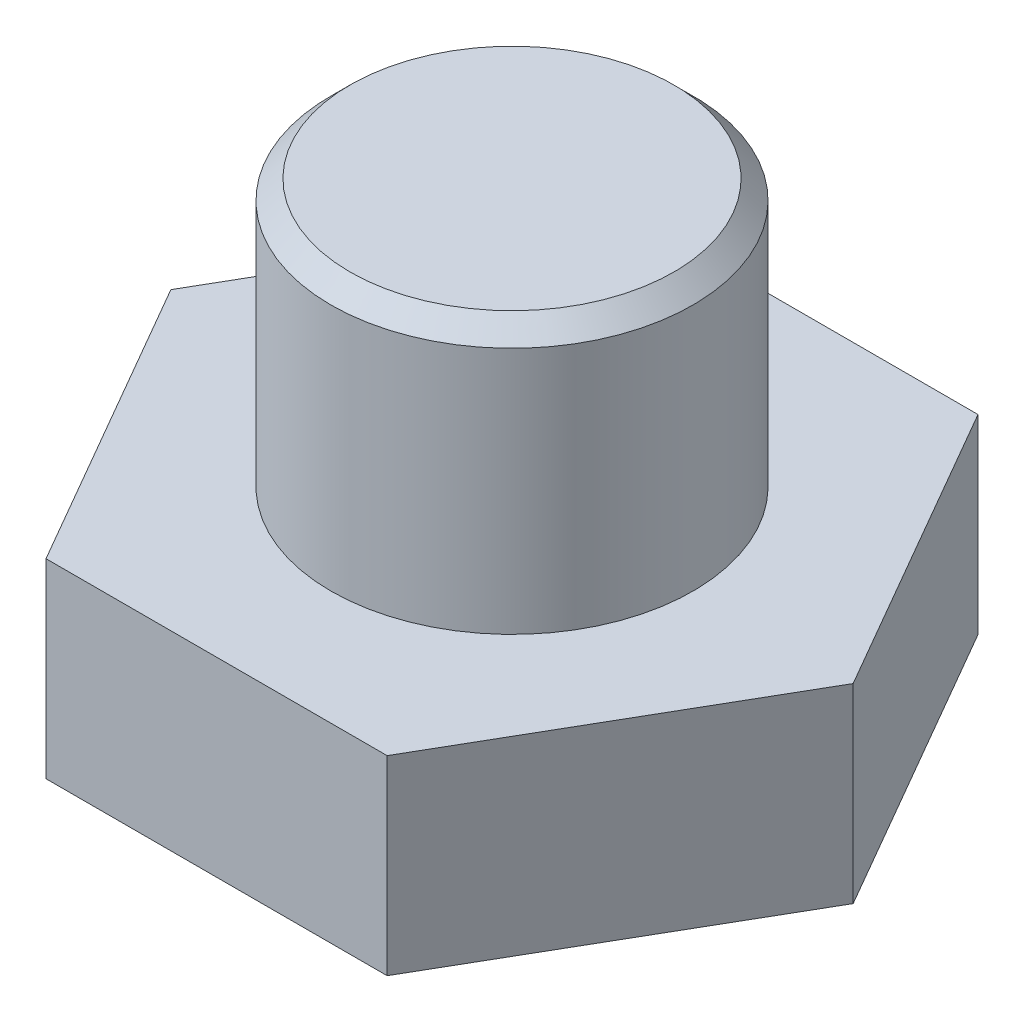
SolidWorks part; units mm, degrees
ref_plane "Front Plane" through (0, 0, 0) normal (0, 0, 1) x (1, 0, 0)
ref_plane "Top Plane" through (0, 0, 0) normal (0, 1, 0) x (1, 0, 0)
ref_plane "Right Plane" through (0, 0, 0) normal (1, 0, 0) x (0, 0, -1)
sketch "Sketch1" plane through (0, 0, 0) normal (0, 1, 0) x (1, 0, 0)
  line L1 (-17.8979, 0) -> (-8.9489, -15.5)
  line L2 (-8.9489, -15.5) -> (8.9489, -15.5)
  line L3 (8.9489, -15.5) -> (17.8979, 0)
  line L4 (17.8979, 0) -> (8.9489, 15.5)
  line L5 (8.9489, 15.5) -> (-8.9489, 15.5)
  line L6 (-8.9489, 15.5) -> (-17.8979, 0)
  circle A0 centre (0, 0) radius 15.5 construction
  dimension "D1" = 31
extrude "Boss-Extrude1" add sketch "Sketch1" against normal blind 10
sketch "Sketch2" plane through (0, 0, 0) normal (0, 1, 0) x (1, 0, 0)
  circle A0 centre (0, 0) radius 9.5
  dimension "D1" = 19
extrude "Boss-Extrude2" add sketch "Sketch2" along normal blind 14
chamfer "Chamfer1" distance 1 angle 45 1 edges at (0, 14, 9.5)
